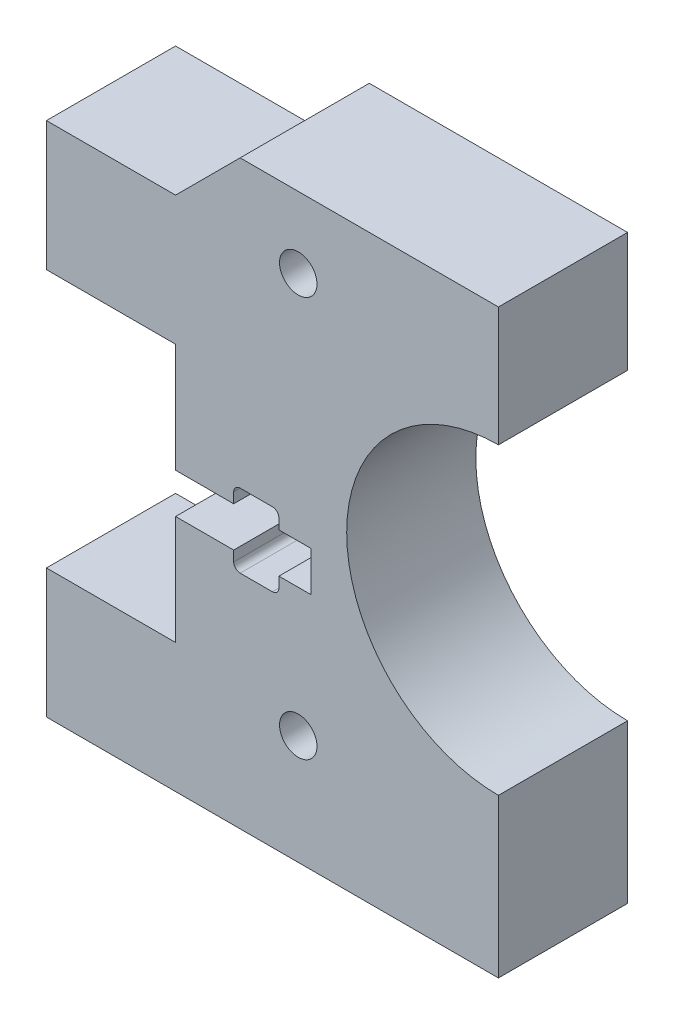
SolidWorks part; units mm, degrees
ref_plane "Front Plane" through (0, 0, 0) normal (0, 0, 1) x (1, 0, 0)
ref_plane "Top Plane" through (0, 0, 0) normal (0, 1, 0) x (1, 0, 0)
ref_plane "Right Plane" through (0, 0, 0) normal (1, 0, 0) x (0, 0, -1)
sketch "Sketch1" plane through (0, 0, 0) normal (0, 0, 1) x (1, 0, 0)
  line L0 (0, 0) -> (0, -50) construction
  line L1 (-10, -40) -> (0, -40) construction
  line L2 (25, -50) -> (25, 0) construction
  line L3 (25, 0) -> (0, 0) construction
  line L4 (0, 0) -> (0, -5)
  line L5 (0, -5) -> (-10, -5)
  line L6 (-10, -5) -> (-10, -15)
  line L7 (-10, -15) -> (0, -15)
  line L8 (0, -15) -> (0, -35)
  line L9 (25, -50) -> (0, -50) construction
  line L10 (0, -50) -> (25, -50)
  line L11 (-10, -35) -> (0, -35)
  line L12 (-10, -45) -> (-10, -35)
  line L13 (0, -45) -> (-10, -45)
  line L14 (25, -50) -> (25, 0)
  line L15 (0, 0) -> (25, 0)
  line L16 (0, -50) -> (0, -45)
  line L17 (-10, -10) -> (0, -10) construction
  line L18 (0, -25) -> (25, -25) construction
  dimension "D1" = 10
  dimension "D3" = 10
  dimension "D6" = 25
  dimension "D2" = 25
  dimension "D4" = 15
extrude "Boss-Extrude1" add sketch "Sketch1" along normal blind 10
sketch "Sketch2" plane through (0, 0, 10) normal (0, 0, 1) x (1, 0, 0)
  line L0 (25, -21) -> (0, -21) construction
  line L1 (25, -50) -> (25, 0) construction
  line L2 (0, -15) -> (0, -35) construction
  line L3 (25, -21) -> (9.5, -5.5) construction
  line L4 (25, -21) -> (9.5, -36.5) construction
  circle A0 centre (25, -21) radius 11.75
  circle A1 centre (9.5, -5.5) radius 1.45
  circle A2 centre (9.5, -36.5) radius 1.45
  point P6 (0, -25)
  dimension "D2" = 23.5
  dimension "D5" = 2.9
  dimension "D1" = 4
  dimension "D3" = 45
  dimension "D4" = 15.5
extrude "motor" cut sketch "Sketch2" against normal through all
sketch "Sketch3" plane through (0, 0, 10) normal (0, 0, 1) x (1, 0, 0)
  line L0 (0, -25) -> (10.5, -25) construction
  line L1 (0, -15) -> (0, -35) construction
  line L2 (10.5, -26.55) -> (10.5, -23.45) construction
  line L3 (10.5, -23.45) -> (0, -23.45) construction
  line L4 (0, -26.55) -> (0, -23.45)
  line L5 (0, -23.45) -> (4.5, -23.45)
  line L6 (4.5, -23.45) -> (4.5, -22.65)
  line L7 (5, -22.15) -> (7.5, -22.15)
  line L8 (8, -22.65) -> (8, -23.45)
  line L9 (8, -23.45) -> (10.5, -23.45)
  line L10 (10.5, -23.45) -> (10.5, -26.55)
  line L11 (10.5, -26.55) -> (0, -26.55) construction
  line L12 (8, -26.55) -> (10.5, -26.55)
  line L13 (8, -27.35) -> (8, -26.55)
  line L14 (5, -27.85) -> (7.5, -27.85)
  line L15 (4.5, -26.55) -> (4.5, -27.35)
  line L16 (0, -26.55) -> (4.5, -26.55)
  arc A0 (5, -27.85) -> (4.5, -27.35) centre (5, -27.35) cw
  arc A1 (8, -27.35) -> (7.5, -27.85) centre (7.5, -27.35) cw
  arc A2 (7.5, -22.15) -> (8, -22.65) centre (7.5, -22.65) cw
  arc A3 (4.5, -22.65) -> (5, -22.15) centre (5, -22.65) cw
  point P18 (4.5, -27.85)
  point P21 (8, -27.85)
  point P24 (8, -22.15)
  point P27 (4.5, -22.15)
  dimension "D6" = 0.5
  dimension "D1" = 1.55
  dimension "D2" = 8
  dimension "D3" = 10.5
  dimension "D4" = 2.85
  dimension "D5" = 3.5
extrude "screw" cut sketch "Sketch3" against normal through all
sketch "Sketch4" plane through (0, 0, 10) normal (0, 0, 1) x (1, 0, 0)
  line L0 (0, -45) -> (25, -45)
  line L1 (25, -50) -> (25, -32.75) construction
  line L2 (25, -45) -> (25, -50)
  line L3 (25, -50) -> (0, -50)
  line L4 (0, -50) -> (0, -45)
  line L5 (0, -5) -> (5, 0)
  line L6 (25, 0) -> (0, 0) construction
  line L7 (5, 0) -> (0, 0)
  line L8 (0, 0) -> (0, -5)
  dimension "D1" = 45
extrude "Cut-Extrude3" cut sketch "Sketch4" against normal through all
equation "\"X-ROD-SPACING\"=45"
equation "\"Y-ROD-SPACING\"=75"
equation "\"Z-ROD-SPACING\"=17.5"
equation "\"Y-BED-OFFSET\"=2"
equation "\"Y-BED-ROD-INSET\"=3.5"
equation "\"T-SLOT-NUT-FILLET-RADIUS\"=0.5"
equation "\"T-SLOT-SCREW-SHAFT-RADIUS\"=1.55"
equation "\"T-SLOT-SCREW-SHAFT-CUTOUT-LENGTH\"=11"
equation "\"T-SLOT-NUT-DEPTH\"=3.5"
equation "\"T-SLOT-NUT-WIDTH\"=2.85"
equation "\"T-SLOT-NUT-END-DISTANCE\"=8"
equation "\"ACRYLIC-THICKNESS\"=10"
equation "\"ACRYLIC-THICKNESS2\"=4.5"
equation "\"ACRYLIC-TAB-CUTOUT-SIZE\"=\"ACRYLIC-THICKNESS\"+\"ACRYLIC-TAB-TOLERANCE\"*2"
equation "\"ACRYLIC-TAB-WIDTH\"=\"ACRYLIC-THICKNESS\""
equation "\"ACRYLIC-M3-HOLE\"=2.9"
equation "\"SMOOTHROD-CAP-SCREW-DISTANCE\"=20"
equation "\"FRAME-WIDTH-INNER\"=370"
equation "\"NEMA17-HOLE-SPACING\"=31"
equation "\"NEMA17-CENTRAL-CUTOUT\"=22.5"
equation "\"Z-BRACKET-REACH\"=55"
equation "\"TOP-BRACKET-SPACING\"=40"
equation "\"SMOOTHROD-X-LENGTH\"=350"
equation "\"SMOOTHROD-Y-LENGTH\"=350"
equation "\"SMOOTHROD-Z-LENGTH\"=350"
equation "\"SMOOTHROD-TIGHTENING-HEADROOM\"=.25"
equation "\"LEADSCREW-Z-LENGTH\"=300"
equation "\"SCREW-LENGTH-FRAME\"=\"ACRYLIC-THICKNESS\" + 10"
equation "\"SCREW-HEAD-RADIUS\"=6"
equation "\"PRINTED-X-SMOOTHROD-DIAMETER\"=8.8"
equation "\"PRINTED-X-SMOOTHROD-CUTOUT\"=10"
equation "\"PRINTED-X-BASE-HEIGHT\"=10"
equation "\"PRINTED-LM8UU-CUTOUT-SIZE\"=15.5"
equation "\"PRINTED-LM8UU-CUTOUT-LENGTH\"=24.5"
equation "\"PRINTED-X-IDLER-HEIGHT\"=16"
equation "\"PSU-MOUNTING-WIDTH\"=95"
equation "\"PSU-MOUNTING-HEIGHT\"=177"
equation "\"D1@Sketch1\"=10"
equation "\"D3@Sketch1\"=10"
equation "\"D1@Boss-Extrude1\"=\"ACRYLIC-THICKNESS\""
equation "\"D2@Sketch2\"=\"NEMA17-CENTRAL-CUTOUT\"+1"
equation "\"D4@Sketch2\"=\"NEMA17-HOLE-SPACING\"/2"
equation "\"D5@Sketch2\"=\"ACRYLIC-M3-HOLE\""
equation "\"D1@Sketch3\"=\"T-SLOT-SCREW-SHAFT-RADIUS\""
equation "\"D4@Sketch3\"=\"T-SLOT-NUT-WIDTH\""
equation "\"D2@Sketch3\"=\"T-SLOT-NUT-END-DISTANCE\""
equation "\"D5@Sketch3\"=\"T-SLOT-NUT-DEPTH\""
equation "\"D6@Sketch3\"=\"T-SLOT-NUT-FILLET-RADIUS\""
